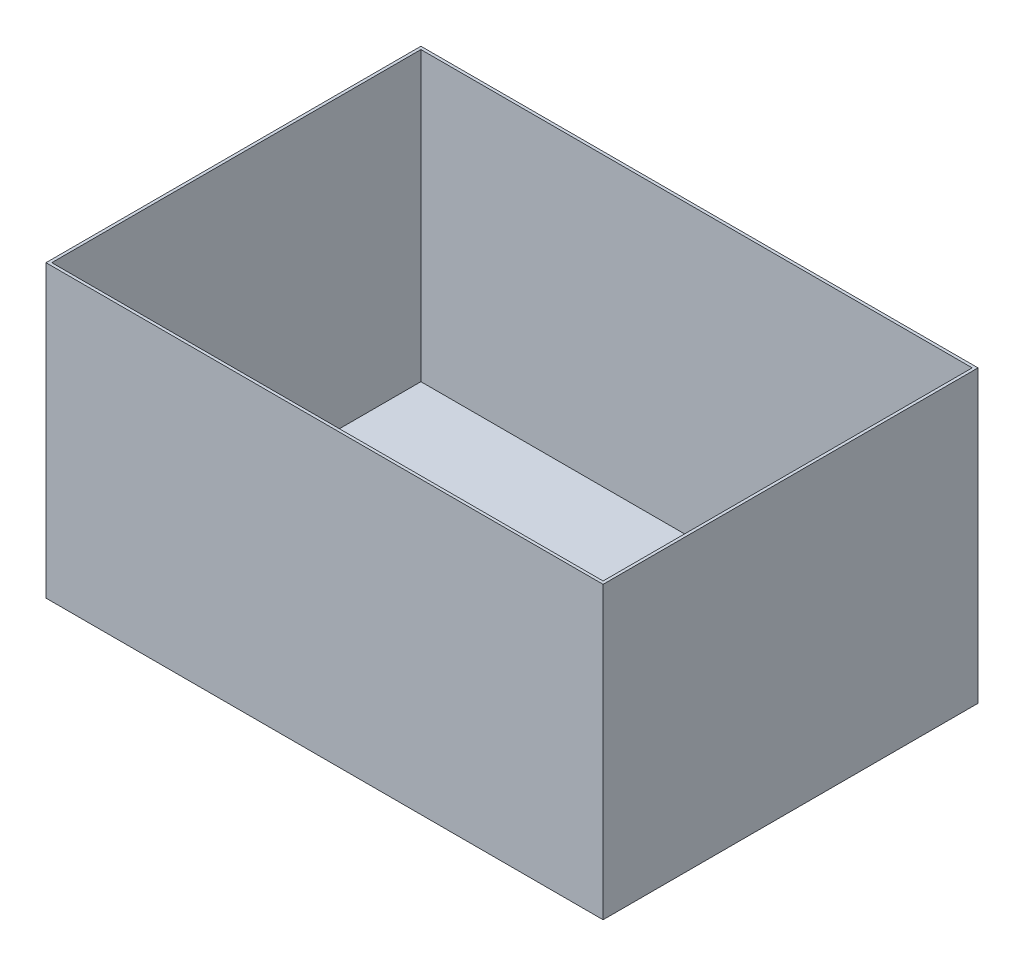
SolidWorks part; units mm, degrees
material "ABS PC"
ref_plane "Front Plane" through (0, 0, 0) normal (0, 0, 1) x (1, 0, 0)
ref_plane "Top Plane" through (0, 0, 0) normal (0, 1, 0) x (1, 0, 0)
ref_plane "Right Plane" through (0, 0, 0) normal (1, 0, 0) x (0, 0, -1)
sketch "Sketch1" plane through (0, 0, 0) normal (0, 1, 0) x (1, 0, 0)
  line L1 (-290.5, 195.5) -> (290.5, 195.5)
  line L2 (-290.5, 195.5) -> (-290.5, -195.5)
  line L3 (-290.5, -195.5) -> (290.5, -195.5)
  line L4 (290.5, 195.5) -> (290.5, -195.5)
  line L5 (-290.5, 195.5) -> (290.5, -195.5) construction
  line L6 (-290.5, -195.5) -> (290.5, 195.5) construction
  point P0 (0, 0)
  dimension "D1" = 391
  dimension "D2" = 581
extrude "Boss-Extrude1" add sketch "Sketch1" along normal mid plane 303
shell "Shell1" thickness 3
